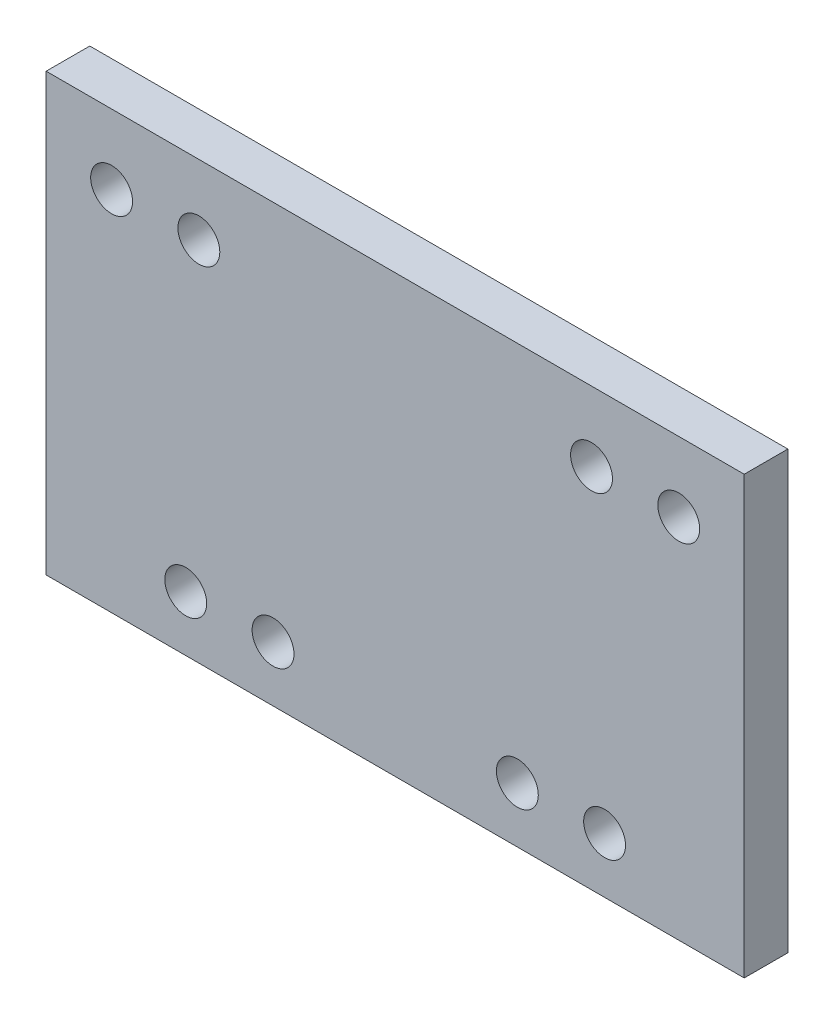
SolidWorks part; units mm, degrees
material "Custom Plastic"
ref_plane "X-Y Datum" through (0, 0, 0) normal (0, 0, 1) x (1, 0, 0)
ref_plane "X-Z Datum" through (0, 0, 0) normal (0, 1, 0) x (1, 0, 0)
ref_plane "Y-Z Datum" through (0, 0, 0) normal (1, 0, 0) x (0, 0, -1)
sketch "Sketch1" plane through (0, 0, 0) normal (0, 0, 1) x (1, 0, 0)
  line L1 (-40, 25) -> (40, 25)
  line L2 (-40, 25) -> (-40, -25)
  line L3 (-40, -25) -> (40, -25)
  line L4 (40, 25) -> (40, -25)
  line L5 (-40, 25) -> (40, -25) construction
  line L6 (-40, -25) -> (40, 25) construction
  point P0 (0, 0)
  dimension "D1" = 80
  dimension "D2" = 50
extrude "Boss-Extrude1" add sketch "Sketch1" along normal blind 5
sketch "Sketch2" plane through (0, 0, 5) normal (0, 0, 1) x (1, 0, 0)
  circle A0 centre (32.5, 17) radius 3.025 construction
  circle A1 centre (22.5, 17) radius 3.025 construction
  circle A2 centre (24, -18.65) radius 3.025 construction
  circle A3 centre (14, -18.65) radius 3.025 construction
  circle A4 centre (-22.5, 17) radius 3.025 construction
  circle A5 centre (-14, -18.65) radius 3.025 construction
  circle A6 centre (-24, -18.65) radius 3.025 construction
  circle A7 centre (-32.5, 17) radius 3.025 construction
  circle A8 centre (32.5, 17) radius 3.025 construction
  circle A9 centre (22.5, 17) radius 3.025 construction
  circle A10 centre (24, -18.65) radius 3.025 construction
  circle A11 centre (14, -18.65) radius 3.025 construction
  circle A12 centre (-22.5, 17) radius 3.025 construction
  circle A13 centre (-14, -18.65) radius 3.025 construction
  circle A14 centre (-24, -18.65) radius 3.025 construction
  circle A15 centre (-32.5, 17) radius 3.025 construction
hole_wizard "M4 Clearance Hole1" positions "Sketch3" profile "Sketch4" hole size "M4" standard "ANSI Metric" end condition through all
sketch "Sketch3" plane through (0, 0, 5) normal (0, 0, 1) x (1, 0, 0)
  point P0 (-32.5, 17)
  point P3 (-22.5, 17)
  point P6 (-24, -18.65)
  point P9 (-14, -18.65)
  point P12 (14, -18.65)
  point P15 (24, -18.65)
  point P18 (22.5, 17)
  point P21 (32.5, 17)
sketch "Sketch4" plane through (-32.5, 17, 5) normal (1, 0, 0) x (0, -1, 0)
  line L0 (0, 0) -> (0, 5)
  line L1 (0, 5) -> (2.4, 5)
  line L2 (2.4, 5) -> (2.4, 0)
  line L5 (2.4, 0) -> (0, 0)
  line L11 (0, -6.35) -> (0, 107.95) construction
  dimension "Thru Hole Dia." = 4.8
  dimension "Thru Hole Depth" = 5
